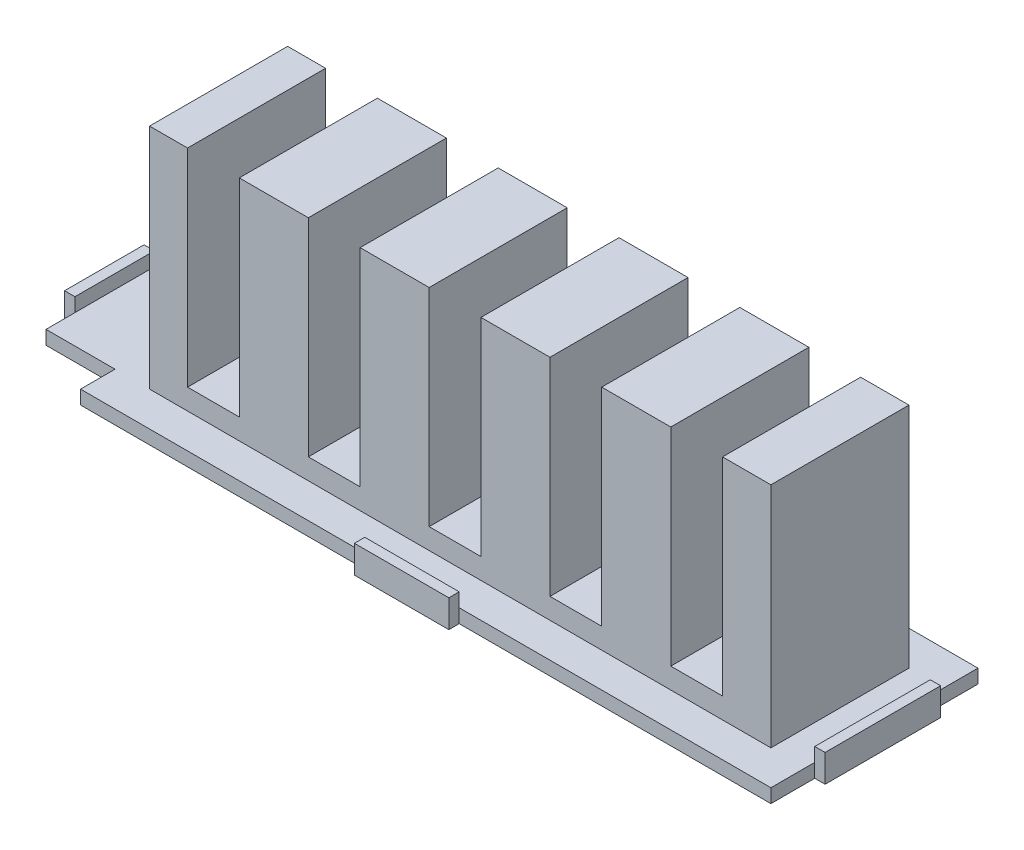
SolidWorks part; units mm, degrees
ref_plane "前视基准面" through (0, 0, 0) normal (0, 0, 1) x (1, 0, 0)
ref_plane "上视基准面" through (0, 0, 0) normal (0, 1, 0) x (1, 0, 0)
ref_plane "右视基准面" through (0, 0, 0) normal (1, 0, 0) x (0, 0, -1)
sketch "草图1" plane through (0, 0, 0) normal (0, 1, 0) x (1, 0, 0)
  line L0 (10, 15) -> (10, 10)
  line L1 (10, 15) -> (110, 15)
  line L2 (10, -15) -> (110, -15)
  line L3 (110, 15) -> (110, -15)
  line L4 (10, -10) -> (0, -10)
  line L5 (10, 10) -> (0, 10)
  line L6 (0, -10) -> (0, 10)
  line L7 (10, -10) -> (10, -15)
  line L16 (12.5, 12.5) -> (107.5, 12.5)
  line L17 (107.5, 12.5) -> (107.5, -12.5)
  line L18 (12.5, -12.5) -> (107.5, -12.5)
  line L19 (12.5, -7.5) -> (12.5, -12.5)
  line L20 (12.5, -7.5) -> (2.5, -7.5)
  line L21 (2.5, -7.5) -> (2.5, 7.5)
  line L22 (12.5, 7.5) -> (2.5, 7.5)
  line L23 (12.5, 12.5) -> (12.5, 7.5)
  point P17 (-58.013, 33.0506)
  dimension "D1" = 30
  dimension "D2" = 100
  dimension "D3" = 10
  dimension "D4" = 5
  dimension "D5" = 5
  dimension "D6" = 2.5
extrude "凸台-拉伸1" add sketch "草图1" along normal blind 2 contours L0 L5 L6 L4 L7 L2 L3 L1
sketch "草图2" plane through (0, 2, 0) normal (0, 1, 0) x (1, 0, 0)
  line L0 (110, 15) -> (110, -15) construction
  line L1 (12.5, 12.5) -> (107.5, 12.5) construction
  line L2 (12.5, 12.5) -> (12.5, -12.5) construction
  line L3 (12.5, -12.5) -> (107.5, -12.5) construction
  line L4 (107.5, 12.5) -> (107.5, -12.5) construction
  line L5 (10, -15) -> (110, -15) construction
  line L6 (10, 15) -> (110, 15) construction
  line L7 (10, 15) -> (10, 10) construction
  line L8 (15, 10) -> (105, 10)
  line L9 (105, 10) -> (105, -10)
  line L10 (15, -10) -> (105, -10)
  line L11 (15, 10) -> (15, -10)
  dimension "D1" = 2.5
  dimension "D2" = 2.5
  dimension "D3" = 2.5
  dimension "D4" = 2.5
  dimension "D5" = 2.5
extrude "凸台-拉伸2" add sketch "草图2" along normal blind 3
sketch "草图3" plane through (0, 5, 0) normal (0, 1, 0) x (1, 0, 0)
  line L0 (105, 10) -> (15, 10) construction
  line L1 (80.5, 10) -> (90.5, 10)
  line L2 (80.5, 10) -> (80.5, -10)
  line L3 (80.5, -10) -> (90.5, -10)
  line L4 (90.5, 10) -> (90.5, -10)
  line L5 (15, -10) -> (105, -10) construction
  line L6 (15, 10) -> (15, -10) construction
  line L7 (63, 10) -> (73, 10)
  line L8 (63, 10) -> (63, -10)
  line L9 (63, -10) -> (73, -10)
  line L10 (73, 10) -> (73, -10)
  line L11 (45.5, 10) -> (55.5, 10)
  line L12 (45.5, 10) -> (45.5, -10)
  line L13 (45.5, -10) -> (55.5, -10)
  line L14 (55.5, 10) -> (55.5, -10)
  line L15 (28, 10) -> (38, 10)
  line L16 (28, 10) -> (28, -10)
  line L17 (28, -10) -> (38, -10)
  line L18 (38, 10) -> (38, -10)
  line L19 (15, 10) -> (20.5, 10)
  line L20 (15, 10) -> (15, -10)
  line L21 (15, -10) -> (20.5, -10)
  line L22 (20.5, 10) -> (20.5, -10)
  line L23 (98, 10) -> (105, 10)
  line L24 (98, 10) -> (98, -10)
  line L25 (98, -10) -> (105, -10)
  line L26 (105, 10) -> (105, -10)
  point P31 (0, 0)
  point P32 (0, 0)
  dimension "D1" = 7
  dimension "D2" = 7.5
  dimension "D3" = 7.5
  dimension "D4" = 7.5
  dimension "D5" = 7.5
  dimension "D6" = 7.5
  dimension "D7" = 10
  dimension "D8" = 10
  dimension "D9" = 10
  dimension "D10" = 10
extrude "凸台-拉伸3" add sketch "草图3" along normal blind 30
sketch "草图4" plane through (15, 0, 0) normal (-1, 0, 0) x (0, 0, 1)
  line L0 (-10, 2) -> (10, 2) construction
  circle A0 centre (0, 7) radius 3.25
  point P4 (0, 0)
  point P5 (0, 0)
  dimension "D1" = 6.5
  dimension "D2" = 5
extrude "切除-拉伸1" cut sketch "草图4" against normal blind 4
sketch "草图5" plane through (0, 0, 0) normal (0, 1, 0) x (1, 0, 0)
  line L0 (10, -15) -> (110, -15) construction
  line L1 (51.1731, -15) -> (64.8513, -15)
  line L2 (51.1731, -15) -> (51.1731, -16.5)
  line L3 (51.1731, -16.5) -> (64.8513, -16.5)
  line L4 (64.8513, -15) -> (64.8513, -16.5)
  line L5 (10, 15) -> (110, 15) construction
  line L6 (51.1731, 15) -> (64.8513, 15)
  line L7 (51.1731, 15) -> (51.1731, 16.5)
  line L8 (51.1731, 16.5) -> (64.8513, 16.5)
  line L9 (64.8513, 15) -> (64.8513, 16.5)
  line L10 (110, 15) -> (110, -15) construction
  line L11 (110, -8.6472) -> (111.5, -8.6472)
  line L12 (110, -8.6472) -> (110, 8.085)
  line L13 (110, 8.085) -> (111.5, 8.085)
  line L14 (111.5, -8.6472) -> (111.5, 8.085)
  line L15 (0, -10) -> (0, 10) construction
  line L16 (0, -5.8064) -> (-1.5, -5.8064)
  line L17 (0, -5.8064) -> (0, 5.7085)
  line L18 (0, 5.7085) -> (-1.5, 5.7085)
  line L19 (-1.5, -5.8064) -> (-1.5, 5.7085)
  point P24 (74.6063, 16.5)
  point P25 (63.7216, -16.5064)
  point P26 (64.8513, 16.5)
  point P27 (51.1731, 16.5)
  dimension "D1" = 1.5
  dimension "D2" = 1.5
  dimension "D3" = 1.5
  dimension "D4" = 1.5
extrude "凸台-拉伸4" add sketch "草图5" along normal blind 4
